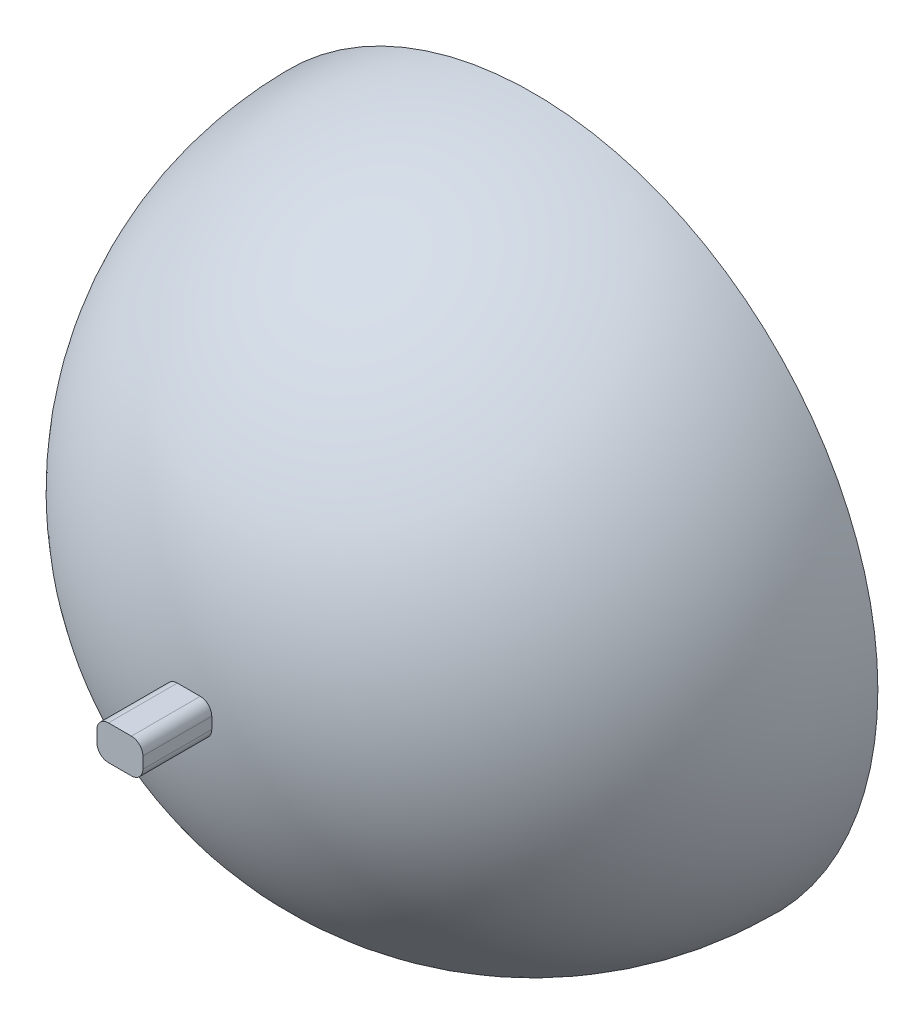
SolidWorks part; units mm, degrees
ref_plane "Front Plane" through (0, 0, 0) normal (0, 0, 1) x (1, 0, 0)
ref_plane "Top Plane" through (0, 0, 0) normal (0, 1, 0) x (1, 0, 0)
ref_plane "Right Plane" through (0, 0, 0) normal (1, 0, 0) x (0, 0, -1)
sketch "Sketch3" plane through (0, 0, 0) normal (0, 0, 1) x (1, 0, 0)
  line L0 (0, 0) -> (0, 30) construction
  line L1 (0, 0) -> (0, 30)
  arc A0 (0, 30) -> (0, 0) centre (0, 15) ccw
  dimension "D1" = 30
revolve "Revolve1" add sketch "Sketch3" angle 180 about L0
sketch "Sketch11" plane through (0, 0, 0) normal (1, 0, 0) x (0, 0, -1)
  line L1 (-15, 15) -> (-18, 15)
  line L2 (-15, 15) -> (-15, 13.5)
  line L3 (-15, 13.5) -> (-18, 13.5)
  line L4 (-18, 15) -> (-18, 13.5)
  arc A0 (0, 30) -> (0, 0) centre (0, 15) ccw construction
  dimension "D1" = 3
  dimension "D2" = 1.5
extrude "Boss-Extrude4" add sketch "Sketch11" along normal mid plane 2 separate body
fillet "Fillet1" radius 0.5 4 edges at (-1, 15, 16.5) (-1, 13.5, 16.5) (1, 15, 16.5) (1, 13.5, 16.5)
